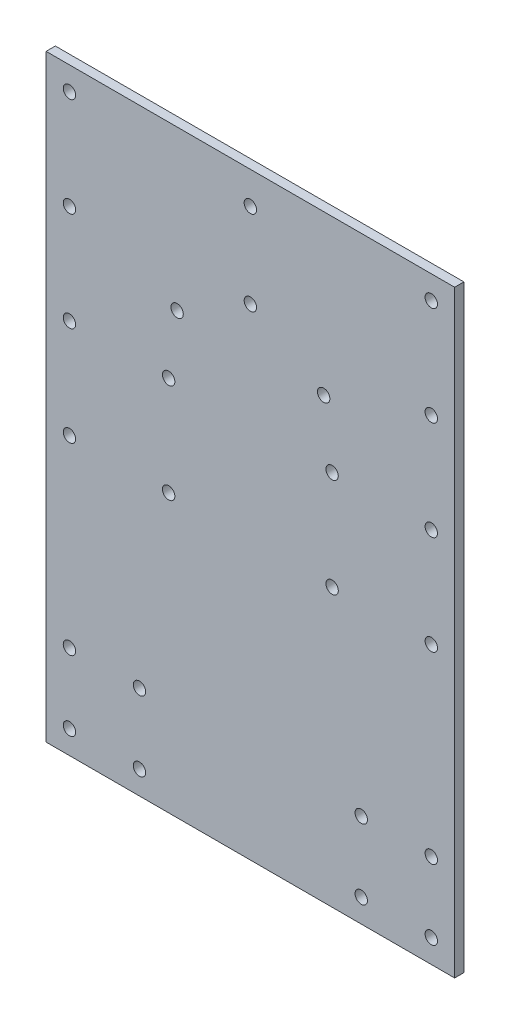
SolidWorks part; units mm, degrees
ref_plane "Front Plane" through (0, 0, 0) normal (0, 0, 1) x (1, 0, 0)
ref_plane "Top Plane" through (0, 0, 0) normal (0, 1, 0) x (1, 0, 0)
ref_plane "Right Plane" through (0, 0, 0) normal (1, 0, 0) x (0, 0, -1)
sketch "Sketch1" plane through (0, 0, 0) normal (0, 0, 1) x (1, 0, 0)
  line L0 (0, 102.5) -> (0, -102.5) construction
  line L1 (-70, -102.5) -> (70, -102.5)
  line L2 (-70, -102.5) -> (-70, 102.5)
  line L3 (-70, 102.5) -> (70, 102.5)
  line L4 (70, -102.5) -> (70, 102.5)
  line L5 (-70, -102.5) -> (70, 102.5) construction
  line L6 (-70, 102.5) -> (70, -102.5) construction
  line L7 (-50, -98.3304) -> (-50, -80.5714) construction
  line L10 (-62, -82.5) -> (-36.3402, -82.5) construction
  circle A0 centre (0, 62.5) radius 33.35 construction
  circle A1 centre (0, 62.5) radius 29 construction
  circle A2 centre (0, 91.5) radius 2.125
  circle A3 centre (25.1147, 48) radius 2.125
  circle A4 centre (-25.1147, 48) radius 2.125
  circle A10 centre (0, 62.5) radius 2.125
  circle A11 centre (-62, -94.5) radius 2.125
  circle A12 centre (-38, -94.5) radius 2.125
  circle A13 centre (-38, -70.5) radius 2.125
  circle A14 centre (-62, -70.5) radius 2.125
  circle A15 centre (38, -94.5) radius 2.125
  circle A16 centre (62, -94.5) radius 2.125
  circle A17 centre (62, -70.5) radius 2.125
  circle A18 centre (38, -70.5) radius 2.125
  point P0 (0, 0)
  point P19 (0, 62.5)
  dimension "D3" = 66.7
  dimension "D4" = 40
  dimension "D5" = 58
  dimension "D6" = 4.25
  dimension "D8" = 4.25
  dimension "D9" = 8
  dimension "D10" = 8
  dimension "D12" = 4.25
  dimension "D1" = 140
  dimension "D2" = 205
  dimension "D11" = 12
  dimension "D13" = 12
  dimension "D7" = 3
extrude "Boss-Extrude1" add sketch "Sketch1" along normal blind 3.175
sketch "Sketch2" plane through (0, 0, 3.175) normal (0, 0, 1) x (1, 0, 0)
  line L0 (70, 102.5) -> (-70, 102.5) construction
  line L1 (-70, 102.5) -> (-70, -102.5) construction
  line L2 (0, 102.5) -> (0, -102.5) construction
  line L3 (-70, -102.5) -> (70, -102.5) construction
  circle A0 centre (-62, 94.5) radius 2.125
  circle A1 centre (-62, 60.5) radius 2.125
  circle A2 centre (-62, 26.5) radius 2.125
  circle A3 centre (-62, -7.5) radius 2.125
  circle A4 centre (-28, 26.5) radius 2.125
  circle A5 centre (-28, -7.5) radius 2.125
  circle A6 centre (28, -7.5) radius 2.125
  circle A7 centre (28, 26.5) radius 2.125
  circle A8 centre (62, -7.5) radius 2.125
  circle A9 centre (62, 26.5) radius 2.125
  circle A10 centre (62, 60.5) radius 2.125
  circle A11 centre (62, 94.5) radius 2.125
  dimension "D1" = 4.25
  dimension "D2" = 8
  dimension "D3" = 8
  dimension "D4" = 4
  dimension "D5" = 2
extrude "Cut-Extrude1" cut sketch "Sketch2" against normal through all
